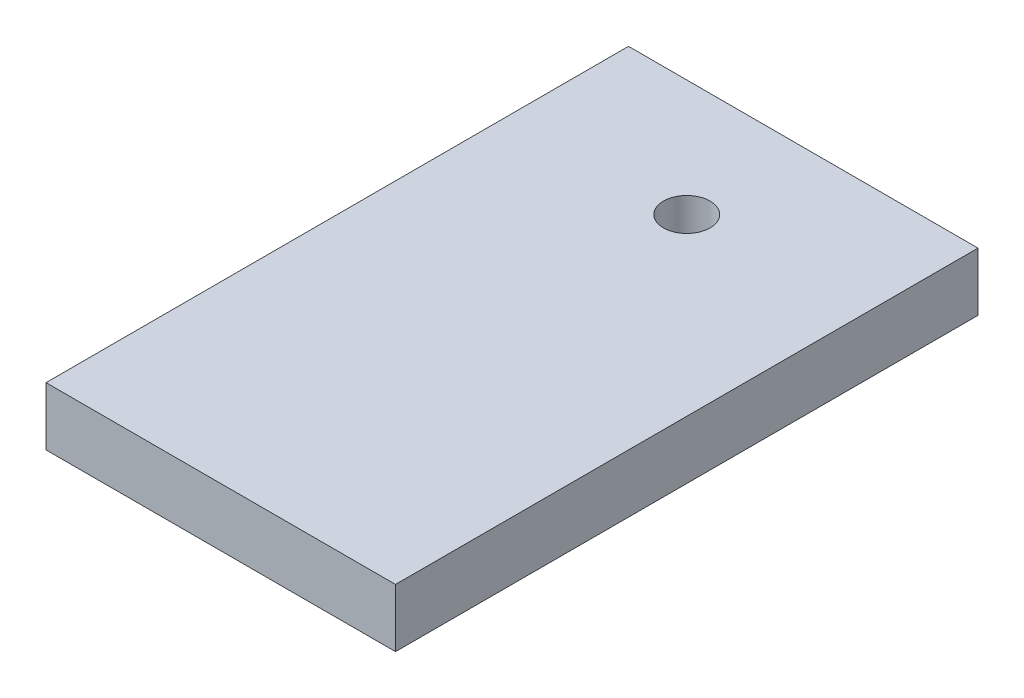
SolidWorks part; units mm, degrees
ref_plane "Front Plane" through (0, 0, 0) normal (0, 0, 1) x (1, 0, 0)
ref_plane "Top Plane" through (0, 0, 0) normal (0, 1, 0) x (1, 0, 0)
ref_plane "Right Plane" through (0, 0, 0) normal (1, 0, 0) x (0, 0, -1)
sketch "Sketch1" plane through (0, 0, 0) normal (0, 1, 0) x (1, 0, 0)
  line L0 (0, 0) -> (15.24, 0)
  line L1 (15.24, 0) -> (15.24, -25.4)
  line L2 (15.24, -25.4) -> (0, -25.4)
  line L3 (0, -25.4) -> (0, 0)
  dimension "D1" = 15.24
  dimension "D2" = 25.4
extrude "Boss-Extrude1" add sketch "Sketch1" against normal blind 2.54
sketch "Sketch2" plane through (0, 0, 0) normal (0, 1, 0) x (1, 0, 0)
  line L0 (0, 0) -> (7.62, 0) construction
  line L1 (15.24, 0) -> (0, 0) construction
  line L2 (7.62, 0) -> (7.62, -5.08) construction
  circle A0 centre (7.62, -5.08) radius 1.016
  dimension "D2" = 2.032
  dimension "D1" = 5.08
extrude "Cut-Extrude1" cut sketch "Sketch2" against normal through all
